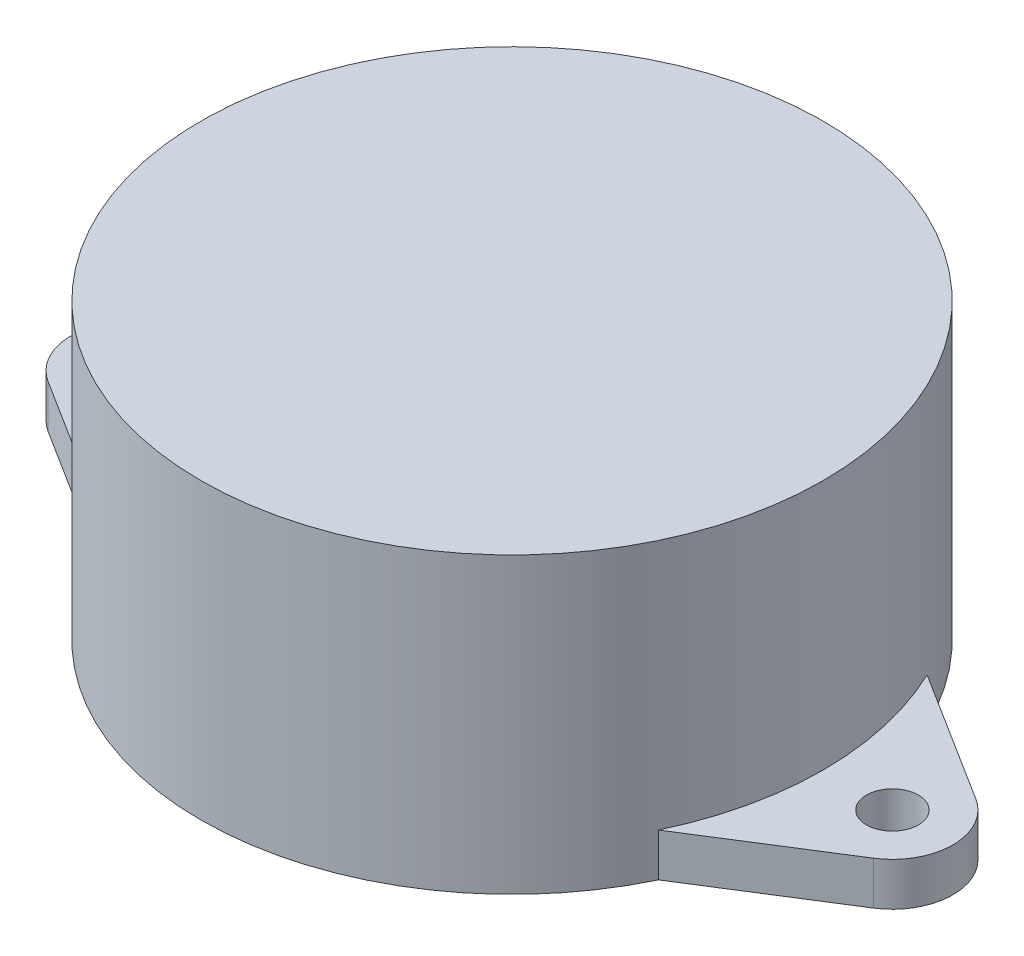
SolidWorks part; units mm, degrees
ref_plane "Front Plane" through (0, 0, 0) normal (0, 0, 1) x (1, 0, 0)
ref_plane "Top Plane" through (0, 0, 0) normal (0, 1, 0) x (1, 0, 0)
ref_plane "Right Plane" through (0, 0, 0) normal (1, 0, 0) x (0, 0, -1)
sketch "Sketch1" plane through (0, 0, 0) normal (0, 1, 0) x (1, 0, 0)
  line L0 (-16.2375, 7.7681) -> (-23.8659, 2.9611)
  line L1 (-23.8659, -2.9611) -> (-16.2375, -7.7681)
  line L2 (-16.2375, 7.7681) -> (0, 18) construction
  line L3 (0, 0) -> (0, 18) construction
  line L4 (16.2375, 7.7681) -> (23.8659, 2.9611)
  line L5 (23.8659, -2.9611) -> (16.2375, -7.7681)
  arc A0 (-16.2375, -7.7681) -> (16.2375, -7.7681) centre (0, 0) ccw
  arc A1 (-23.8659, 2.9611) -> (-23.8659, -2.9611) centre (-22, 0) ccw
  circle A2 centre (-22, 0) radius 1.5
  arc A3 (23.8659, 2.9611) -> (23.8659, -2.9611) centre (22, 0) cw
  circle A4 centre (22, 0) radius 1.5
  arc A5 (16.2375, 7.7681) -> (-16.2375, 7.7681) centre (0, 0) ccw
  dimension "D1" = 36
  dimension "D2" = 3.5
  dimension "D3" = 3
  dimension "D4" = 22
extrude "Boss-Extrude1" add sketch "Sketch1" along normal blind 2.5
sketch "Sketch2" plane through (0, 2.5, 0) normal (0, 1, 0) x (1, 0, 0)
  arc A0 (16.2375, 7.7681) -> (-16.2375, 7.7681) centre (0, 0) ccw construction
  circle A1 centre (0, 0) radius 18
extrude "Boss-Extrude2" add sketch "Sketch2" along normal blind 17 from surface at -2.5 starting at face at (0, 0, 0)
sketch "Sketch3" plane through (0, 0, 0) normal (0, -1, 0) x (1, 0, 0)
  circle A0 centre (0, 0) radius 8
  dimension "D1" = 16
extrude "Boss-Extrude3" add sketch "Sketch3" along normal blind 1.8
sketch "Sketch4" plane through (0, -1.8, 0) normal (0, -1, 0) x (1, 0, 0)
  circle A0 centre (0, 0) radius 2.5
  dimension "D1" = 5
extrude "Boss-Extrude4" add sketch "Sketch4" along normal blind 5
